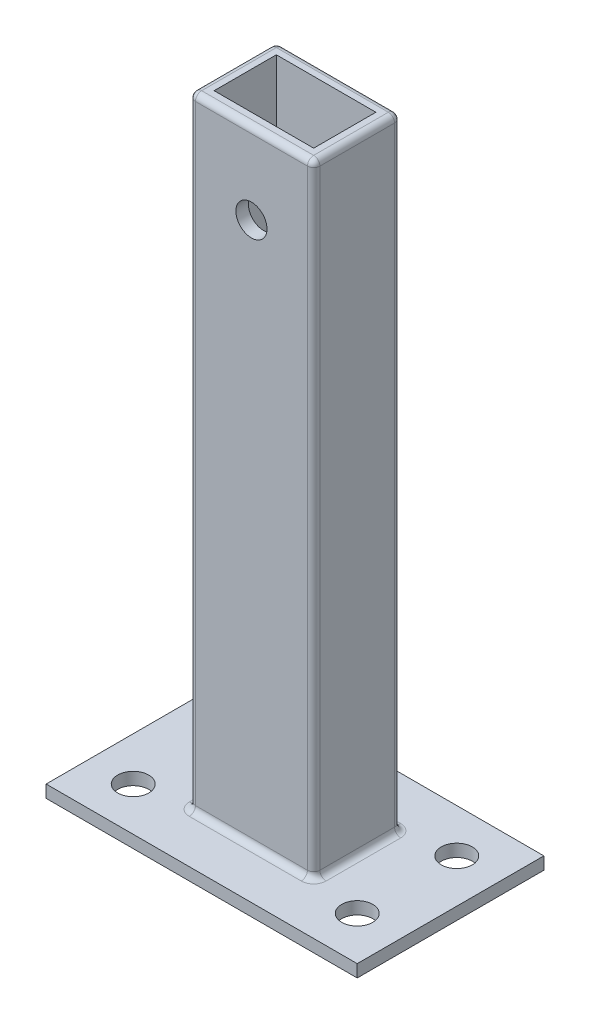
SolidWorks part; units mm, degrees
ref_plane "Front Plane" through (0, 0, 0) normal (0, 0, 1) x (1, 0, 0)
ref_plane "Top Plane" through (0, 0, 0) normal (0, 1, 0) x (1, 0, 0)
ref_plane "Right Plane" through (0, 0, 0) normal (1, 0, 0) x (0, 0, -1)
sketch "Sketch1" plane through (0, 0, 0) normal (0, 1, 0) x (1, 0, 0)
  line L1 (-10, 7) -> (10, 7)
  line L2 (-10, 7) -> (-10, -7)
  line L3 (-10, -7) -> (10, -7)
  line L4 (10, 7) -> (10, -7)
  line L5 (-10, 7) -> (10, -7) construction
  line L6 (-10, -7) -> (10, 7) construction
  line L7 (-8, 5) -> (8, 5)
  line L8 (-8, 5) -> (-8, -5)
  line L9 (-8, -5) -> (8, -5)
  line L10 (8, 5) -> (8, -5)
  line L11 (-8, 5) -> (8, -5) construction
  line L12 (-8, -5) -> (8, 5) construction
  point P0 (0, 0)
  point P6 (0, 0)
  dimension "D1" = 14
  dimension "D2" = 20
  dimension "D3" = 2
  dimension "D4" = 2
extrude "Boss-Extrude1" add sketch "Sketch1" along normal blind 100
sketch "Sketch2" plane through (0, 0, 0) normal (0, -1, 0) x (-1, 0, 0)
  line L1 (25, -15) -> (-25, -15)
  line L2 (25, -15) -> (25, 15)
  line L3 (25, 15) -> (-25, 15)
  line L4 (-25, -15) -> (-25, 15)
  line L5 (25, -15) -> (-25, 15) construction
  line L6 (25, 15) -> (-25, -15) construction
  point P0 (0, 0)
  dimension "D1" = 30
  dimension "D2" = 50
extrude "Boss-Extrude2" add sketch "Sketch2" along normal blind 2
sketch "Sketch3" plane through (0, 0, 0) normal (0, 1, 0) x (1, 0, 0)
  line L0 (25, 15) -> (25, -15) construction
  line L1 (25, -15) -> (-25, -15) construction
  line L3 (0, 0) -> (18, 0) construction
  line L4 (0, 0) -> (0, -13.7658) construction
  circle A0 centre (18, -8) radius 2.5
  circle A1 centre (18, 8) radius 2.5
  circle A2 centre (-18, -8) radius 2.5
  circle A3 centre (-18, 8) radius 2.5
  dimension "D1" = 7
  dimension "D2" = 7
extrude "Cut-Extrude1" cut sketch "Sketch3" against normal blind 2
sketch "Sketch4" plane through (0, 0, 7) normal (0, 0, 1) x (1, 0, 0)
  line L0 (-10, 100) -> (10, 100) construction
  circle A0 centre (0, 87) radius 2.5
  dimension "D1" = 13
  dimension "D2" = 5
extrude "Cut-Extrude2" cut sketch "Sketch4" against normal through all
fillet "Fillet1" radius 1 12 edges at (0, 0, 7) (10, 0, 0) (-10, 0, 0) (0, 0, -7) (10, 50, -7) (-10, 50, -7) (10, 50, 7) (10, 100, 0) (0, 100, -7) (-10, 100, 0) (-10, 50, 7) (0, 100, 7)
